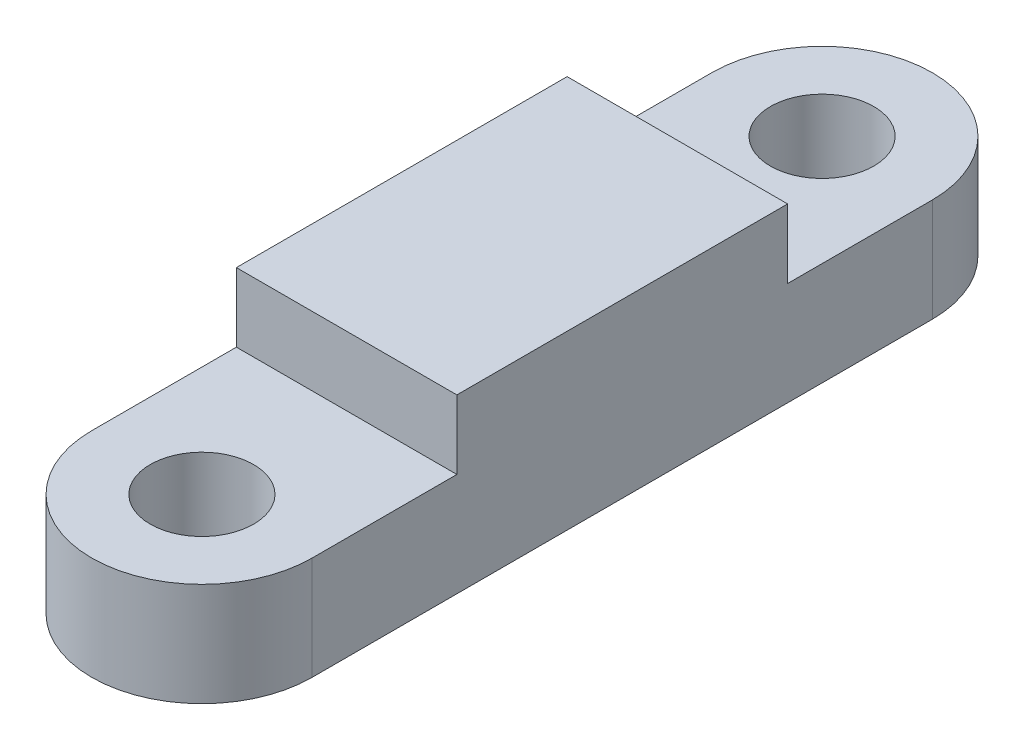
SolidWorks part; units mm, degrees
ref_plane "Front Plane" through (0, 0, 0) normal (0, 0, 1) x (1, 0, 0)
ref_plane "Top Plane" through (0, 0, 0) normal (0, 1, 0) x (1, 0, 0)
ref_plane "Right Plane" through (0, 0, 0) normal (1, 0, 0) x (0, 0, -1)
sketch "Sketch1" plane through (0, 0, 0) normal (0, 1, 0) x (1, 0, 0)
  line L0 (0, 10.6) -> (0, -1.6) construction
  line L1 (-1.6, 9) -> (-1.6, 0)
  line L2 (1.6, 9) -> (1.6, 0)
  circle A0 centre (0, 9) radius 0.75
  circle A1 centre (0, 0) radius 0.75
  arc A2 (1.6, 9) -> (-1.6, 9) centre (0, 9) ccw
  arc A3 (-1.6, 0) -> (1.6, 0) centre (0, 0) ccw
  dimension "D1" = 9
extrude "Boss-Extrude1" add sketch "Sketch1" along normal blind 1.5
sketch "Sketch2" plane through (0, 1.5, 0) normal (0, 1, 0) x (1, 0, 0)
  line L0 (-1.6, 4.5) -> (1.6, 4.5) construction
  line L1 (-1.6, 9) -> (-1.6, 0) construction
  line L2 (1.6, 0) -> (1.6, 9) construction
  line L3 (-1.6, 2.1) -> (1.6, 2.1)
  line L4 (-1.6, 6.9) -> (1.6, 6.9)
  line L5 (-1.6, 6.9) -> (-1.6, 2.1)
  line L6 (1.6, 6.9) -> (1.6, 2.1)
  dimension "D1" = 2.4
  dimension "D2" = 2.4
extrude "Boss-Extrude2" add sketch "Sketch2" along normal blind 1
